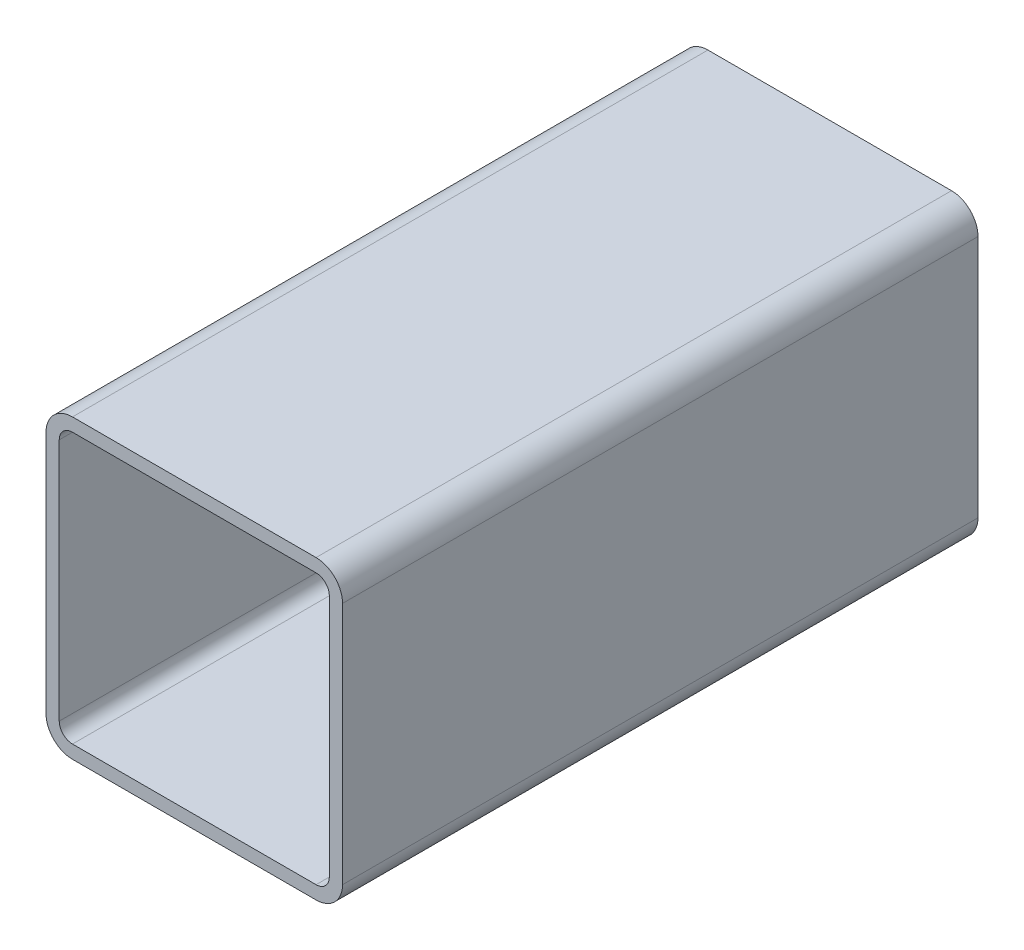
SolidWorks part; units mm, degrees
ref_plane "Front Plane" through (0, 0, 0) normal (0, 0, 1) x (1, 0, 0)
ref_plane "Top Plane" through (0, 0, 0) normal (0, 1, 0) x (1, 0, 0)
ref_plane "Right Plane" through (0, 0, 0) normal (1, 0, 0) x (0, 0, -1)
sketch "Sketch1" plane through (0, 0, 0) normal (0, 0, 1) x (1, 0, 0)
  line L0 (6.35, 3.175) -> (64.77, 3.175)
  line L1 (6.35, 0) -> (64.77, 0)
  line L2 (0, 6.35) -> (0, 64.77)
  line L3 (6.35, 71.12) -> (64.77, 71.12)
  line L4 (71.12, 6.35) -> (71.12, 64.77)
  line L5 (67.945, 6.35) -> (67.945, 64.77)
  line L6 (6.35, 67.945) -> (64.77, 67.945)
  line L7 (3.175, 6.35) -> (3.175, 64.77)
  arc A0 (0, 6.35) -> (6.35, 0) centre (6.35, 6.35) ccw
  arc A1 (64.77, 0) -> (71.12, 6.35) centre (64.77, 6.35) ccw
  arc A2 (71.12, 64.77) -> (64.77, 71.12) centre (64.77, 64.77) ccw
  arc A3 (6.35, 71.12) -> (0, 64.77) centre (6.35, 64.77) ccw
  arc A4 (64.77, 3.175) -> (67.945, 6.35) centre (64.77, 6.35) ccw
  arc A5 (67.945, 64.77) -> (64.77, 67.945) centre (64.77, 64.77) ccw
  arc A6 (6.35, 67.945) -> (3.175, 64.77) centre (6.35, 64.77) ccw
  arc A7 (3.175, 6.35) -> (6.35, 3.175) centre (6.35, 6.35) ccw
  point P7 (0, 0)
  point P12 (71.12, 71.12)
  point P15 (0, 71.12)
  dimension "D3" = 6.35
  dimension "D1" = 71.12
  dimension "D2" = 71.12
  dimension "D4" = 3.175
extrude "Boss-Extrude1" add sketch "Sketch1" along normal blind 2070.1
sketch "Sketch2" plane through (0, 0, 0) normal (0, 1, 0) x (1, 0, 0)
  line L0 (35.56, 0) -> (35.56, -203.2) construction
  line L1 (64.77, 0) -> (6.35, 0) construction
  circle A0 centre (35.56, -101.6) radius 6.35
  circle A1 centre (35.56, -279.4) radius 6.35
  dimension "D1" = 12.7
  dimension "D2" = 12.7
  dimension "D3" = 279.4
  dimension "D4" = 101.6
extrude "Cut-Extrude1" cut sketch "Sketch2" along normal through all
sketch "Sketch3" plane through (0, 0, 0) normal (-1, 0, 0) x (0, 0, 1)
  line L0 (0, 64.77) -> (0, 6.35) construction
  line L1 (0, 35.56) -> (80.0504, 35.56) construction
  circle A0 centre (12.7, 53.975) radius 3.2743
  circle A1 centre (12.7, 17.145) radius 3.2743
  circle A2 centre (63.5, 17.145) radius 3.2743
  circle A3 centre (63.5, 53.975) radius 3.2743
  dimension "D1" = 50.8
  dimension "D2" = 36.83
  dimension "D3" = 12.7
  dimension "D4" = 18.415
extrude "Cut-Extrude2" cut sketch "Sketch3" against normal through all
sketch "Sketch4" plane through (0, 71.12, 0) normal (0, 1, 0) x (1, 0, 0)
  line L2 (35.56, -2070.1) -> (35.56, -537.9414) construction
  line L3 (64.77, -2070.1) -> (6.35, -2070.1) construction
  circle A0 centre (13.335, -1508.125) radius 1.905
  circle A1 centre (57.785, -1508.125) radius 1.905
  circle A2 centre (57.785, -1565.275) radius 1.905
  circle A3 centre (13.335, -1565.275) radius 1.905
  circle A4 centre (13.335, -1133.475) radius 1.905
  circle A5 centre (57.785, -1133.475) radius 1.905
  circle A6 centre (57.785, -1190.625) radius 1.905
  circle A7 centre (13.335, -1190.625) radius 1.905
  dimension "D2" = 3.81
  dimension "D7" = 3.81
  dimension "D1" = 504.825
  dimension "D3" = 44.45
  dimension "D4" = 57.15
  dimension "D5" = 22.225
  dimension "D6" = 374.65
  dimension "D8" = 44.45
  dimension "D9" = 57.15
  dimension "D10" = 22.225
extrude "Cut-Extrude3" cut sketch "Sketch4" against normal up to next
sketch "Sketch5" plane through (0, 0, 0) normal (0, 0, -1) x (-1, 0, 0)
  line L4 (0, 6.35) -> (0, 64.77)
  line L5 (-6.35, 71.12) -> (-64.77, 71.12)
  line L6 (-71.12, 64.77) -> (-71.12, 6.35)
  line L7 (-64.77, 0) -> (-6.35, 0)
  line L8 (0, 6.35) -> (0, 64.77)
  line L9 (-6.35, 71.12) -> (-64.77, 71.12)
  line L10 (-71.12, 64.77) -> (-71.12, 6.35)
  line L11 (-64.77, 0) -> (-6.35, 0)
  arc A4 (-6.35, 0) -> (0, 6.35) centre (-6.35, 6.35) ccw
  arc A5 (0, 64.77) -> (-6.35, 71.12) centre (-6.35, 64.77) ccw
  arc A6 (-64.77, 71.12) -> (-71.12, 64.77) centre (-64.77, 64.77) ccw
  arc A7 (-71.12, 6.35) -> (-64.77, 0) centre (-64.77, 6.35) ccw
  arc A8 (-6.35, 0) -> (0, 6.35) centre (-6.35, 6.35) ccw
  arc A9 (0, 64.77) -> (-6.35, 71.12) centre (-6.35, 64.77) ccw
  arc A10 (-64.77, 71.12) -> (-71.12, 64.77) centre (-64.77, 64.77) ccw
  arc A11 (-71.12, 6.35) -> (-64.77, 0) centre (-64.77, 6.35) ccw
  dimension "D1" = 0
extrude "Cut-Extrude4" cut sketch "Sketch5" against normal offset from surface (1917.7 mm away) 152.4 up to face at (35.56, 35.56, 2070.1)
equation "\"D4@Sketch3\"=\"D2@Sketch3\"/2"
equation "\"D5@Sketch4\"=\"D3@Sketch4\"/2"
equation "\"D10@Sketch4\"=\"D8@Sketch4\"/2"
